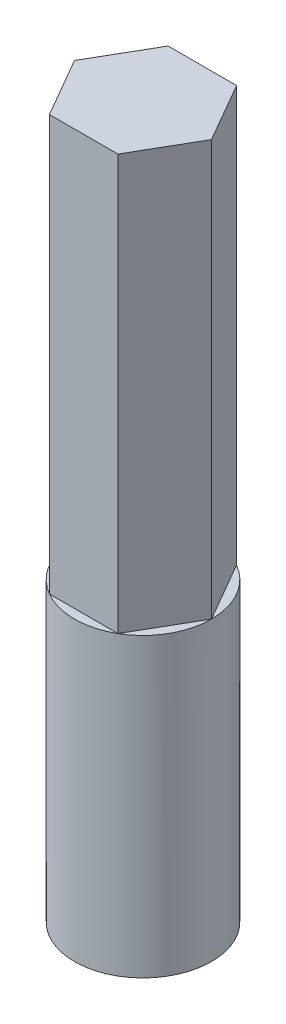
SolidWorks part; units mm, degrees
material "6061 Alloy"
ref_plane "Front Plane" through (0, 0, 0) normal (0, 0, 1) x (1, 0, 0)
ref_plane "Top Plane" through (0, 0, 0) normal (0, 1, 0) x (1, 0, 0)
ref_plane "Right Plane" through (0, 0, 0) normal (1, 0, 0) x (0, 0, -1)
sketch "Sketch3" plane through (0, 0, 0) normal (0, 1, 0) x (1, 0, 0)
  line L1 (7.3323, 0) -> (3.6662, 6.35)
  line L2 (3.6662, 6.35) -> (-3.6662, 6.35)
  line L3 (-3.6662, 6.35) -> (-7.3323, 0)
  line L4 (-7.3323, 0) -> (-3.6662, -6.35)
  line L5 (-3.6662, -6.35) -> (3.6662, -6.35)
  line L6 (3.6662, -6.35) -> (7.3323, 0)
  circle A0 centre (0, 0) radius 6.35 construction
  dimension "D1" = 12.7
extrude "Boss-Extrude1" add sketch "Sketch3" along normal blind 44.45
sketch "Sketch4" plane through (0, 0, 0) normal (0, -1, 0) x (1, 0, 0)
  circle A0 centre (0, 0) radius 7.3323
extrude "Boss-Extrude2" add sketch "Sketch4" along normal blind 31.75
